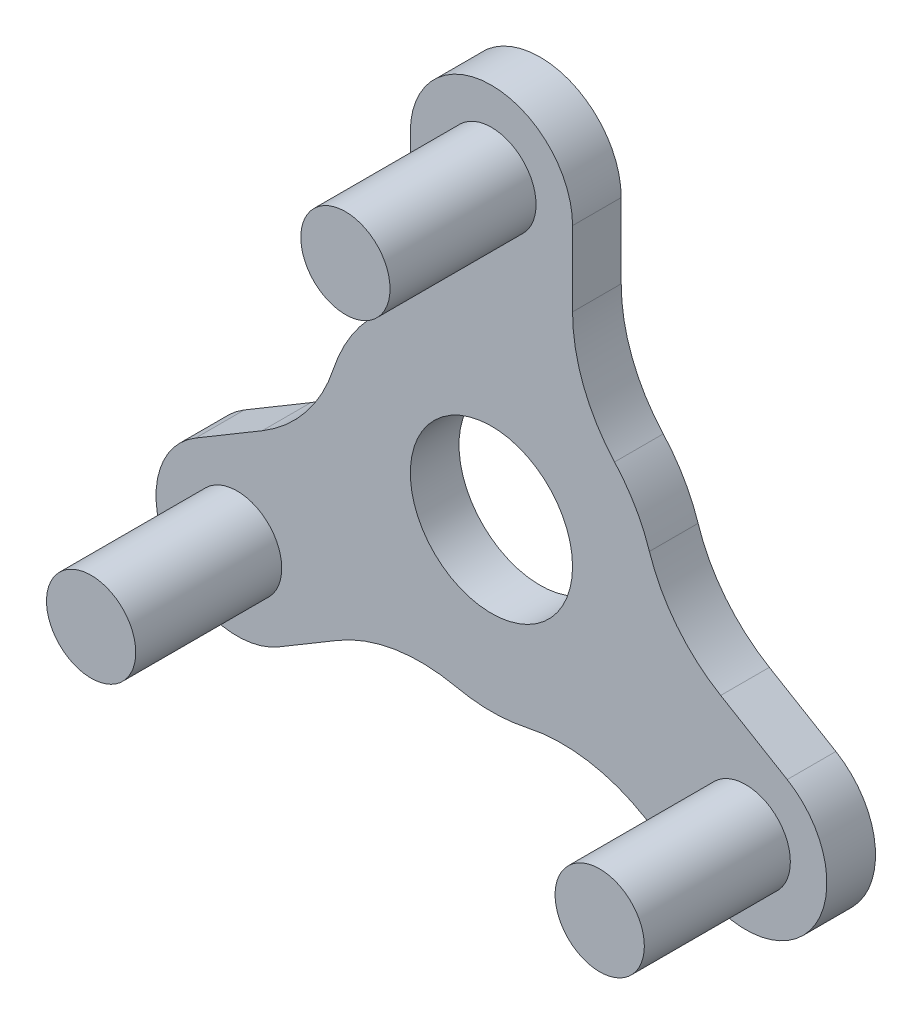
SolidWorks part; units mm, degrees
ref_plane "Alzado" through (0, 0, 0) normal (0, 0, 1) x (1, 0, 0)
ref_plane "Planta" through (0, 0, 0) normal (0, 1, 0) x (1, 0, 0)
ref_plane "Vista lateral" through (0, 0, 0) normal (1, 0, 0) x (0, 0, -1)
sketch "Croquis1" plane through (0, 0, 0) normal (0, 0, 1) x (1, 0, 0)
  line L0 (-18.2318, -4.7531) -> (-10.2435, 0)
  line L1 (-13.1183, -13.3469) -> (-5.359, -8.7299)
  line L2 (13.1183, -13.3469) -> (5.359, -8.7299)
  line L3 (-13.1183, -13.3469) -> (-18.2318, -4.7531)
  line L7 (13.1183, -13.3469) -> (18.2318, -4.7531)
  line L11 (-5, 18.2) -> (5, 18.2)
  line L15 (18.2318, -4.7531) -> (10.2435, 0)
  line L16 (-5, 18.2) -> (-5, 8.9404)
  line L17 (5, 18.2) -> (5, 8.9404)
  circle A0 centre (0, 18.2) radius 5
  circle A1 centre (15.6751, -9.05) radius 5
  circle A2 centre (-15.6751, -9.05) radius 5
  circle A3 centre (0, 0) radius 10.2435
  dimension "D7" = 10
  dimension "D8" = 10
  dimension "D9" = 10
  dimension "D1" = 90
  dimension "D2" = 90
  dimension "D3" = 90
  dimension "D4" = 18.1
  dimension "D5" = 18.1
  dimension "D6" = 18.2
  dimension "D10" = 90
  dimension "D11" = 90
  dimension "D12" = 90
extrude "Saliente-Extruir1" add sketch "Croquis1" along normal blind 3 contours L3 A2 | L3 A2 | A3 L0 A2 L1 | A3 | A3 L2 A1 L15 | A3 L17 A0 L16 | L11 A0 | L11 A0
sketch "Croquis2" plane through (0, 0, 3) normal (0, 0, 1) x (1, 0, 0)
  circle A0 centre (0, 18.2) radius 2.75
  circle A1 centre (15.6751, -9.05) radius 2.75
  circle A2 centre (-15.6751, -9.05) radius 2.75
  dimension "D1" = 5.5
  dimension "D2" = 5.5
  dimension "D3" = 5.5
sketch "Croquis3" plane through (0, 0, 3) normal (0, 0, 1) x (1, 0, 0)
  circle A0 centre (0, 0) radius 5
  dimension "D1" = 10
extrude "Cortar-Extruir2" cut sketch "Croquis3" against normal blind 10
fillet "Redondeo1" radius 10 6 edges at (-5.359, -8.7299, 1.5) (5.359, -8.7299, 1.5) (10.2435, 0, 1.5) (5, 8.9404, 1.5) (-5, 8.9404, 1.5) (-10.2435, 0, 1.5)
extrude "Saliente-Extruir2" add sketch "Croquis2" along normal blind 9
